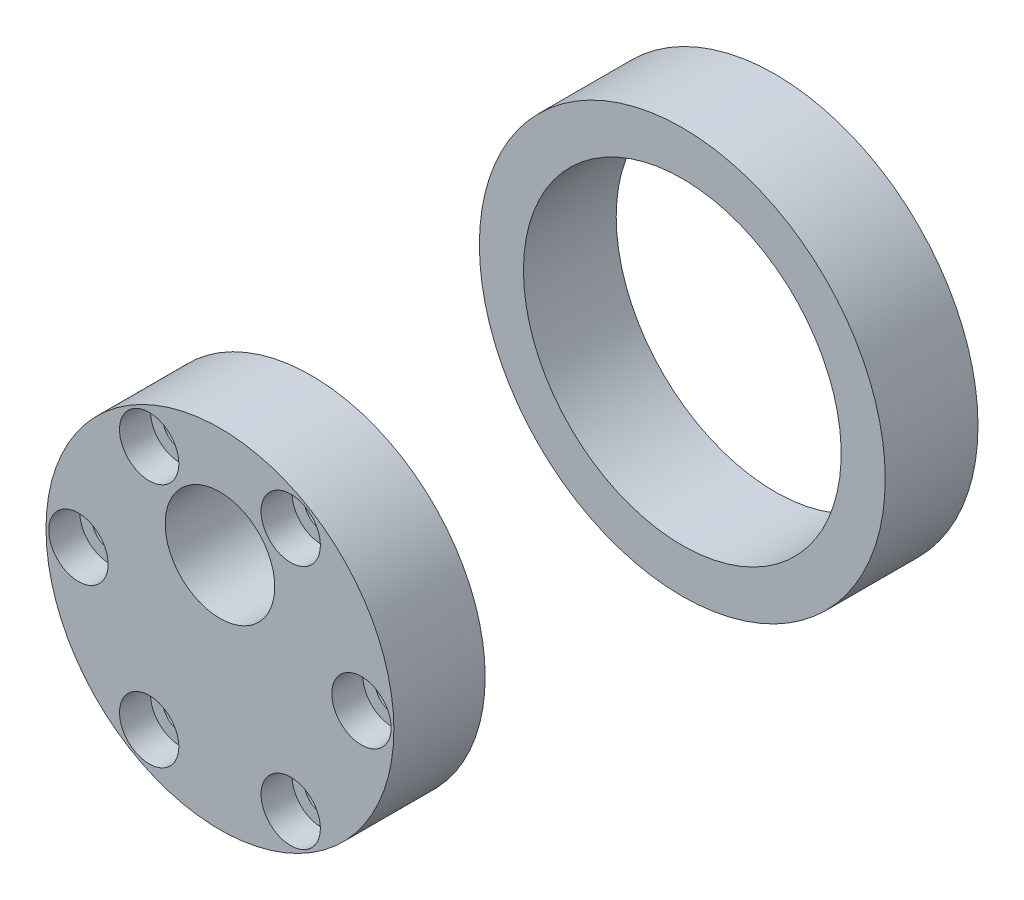
SolidWorks part; units mm, degrees
ref_plane "Front Plane" through (0, 0, 0) normal (0, 0, 1) x (1, 0, 0)
ref_plane "Top Plane" through (0, 0, 0) normal (0, 1, 0) x (1, 0, 0)
ref_plane "Right Plane" through (0, 0, 0) normal (1, 0, 0) x (0, 0, -1)
sketch "Sketch1" plane through (0, 0, 0) normal (0, 0, 1) x (1, 0, 0)
  line L0 (0, 0) -> (0, 7) construction
  line L1 (0, 0) -> (15.5, 0) construction
  circle A0 centre (0, 0) radius 19.05
  circle A1 centre (0, 0) radius 15.5 construction
  circle A2 centre (0, 7) radius 6
  circle A3 centre (15.5, 0) radius 1.905
  circle A4 centre (7.75, -13.4234) radius 1.905
  circle A5 centre (-7.75, -13.4234) radius 1.905
  circle A6 centre (-15.5, 0) radius 1.905
  circle A7 centre (-7.75, 13.4234) radius 1.905
  circle A8 centre (7.75, 13.4234) radius 1.905
  point P20 (0, 0)
  dimension "D1" = 38.1
  dimension "D2" = 31
  dimension "D4" = 12
  dimension "D5" = 3.81
  dimension "D3" = 7
  dimension "D6" = 6
extrude "Face Plate" add sketch "Sketch1" along normal blind 10
hole_wizard "CBORE for M3 Hex Socket Head Cap Screw1" positions "Sketch4" profile "Sketch3" counterbore size "M3" standard "ISO"
sketch "Sketch4" plane through (0, 0, 10) normal (0, 0, 1) x (1, 0, 0)
  point P0 (1.1493, -7.9902)
  point P1 (-7.75, -13.4234)
  point P4 (-15.5, 0)
  point P7 (-7.75, 13.4234)
  point P10 (7.75, 13.4234)
  point P13 (15.5, 0)
  point P16 (7.75, -13.4234)
sketch "Sketch3" plane through (7.75, -13.4234, 10) normal (1, 0, 0) x (0, -1, 0)
  line L0 (0, 0) -> (0, 10)
  line L1 (0, 10) -> (1.7, 10)
  line L3 (1.7, 10) -> (1.7, 3.4)
  line L4 (1.7, 3.4) -> (3.25, 3.4)
  line L5 (3.25, 3.4) -> (3.25, 0)
  line L7 (3.25, 0) -> (0, 0)
  line L11 (0, -6.35) -> (0, 107.95) construction
  dimension "Thru Hole Dia." = 3.4
  dimension "Thru Hole Depth" = 10
  dimension "C'Bore Dia." = 6.5
  dimension "C'Bore Depth" = 3.4
ref_plane "Bracket Plane" through (0, 0, -40.64) normal (0, 0, -1) x (-1, 0, 0)
sketch "Sketch5" plane through (0, 0, -40.64) normal (0, 0, -1) x (-1, 0, 0)
  circle A0 centre (0, 0) radius 17.4
  circle A1 centre (0, 0) radius 22.225
  dimension "D1" = 34.8
  dimension "D2" = 44.45
extrude "Boss-Extrude1" add sketch "Sketch5" along normal blind 10.16 separate body
